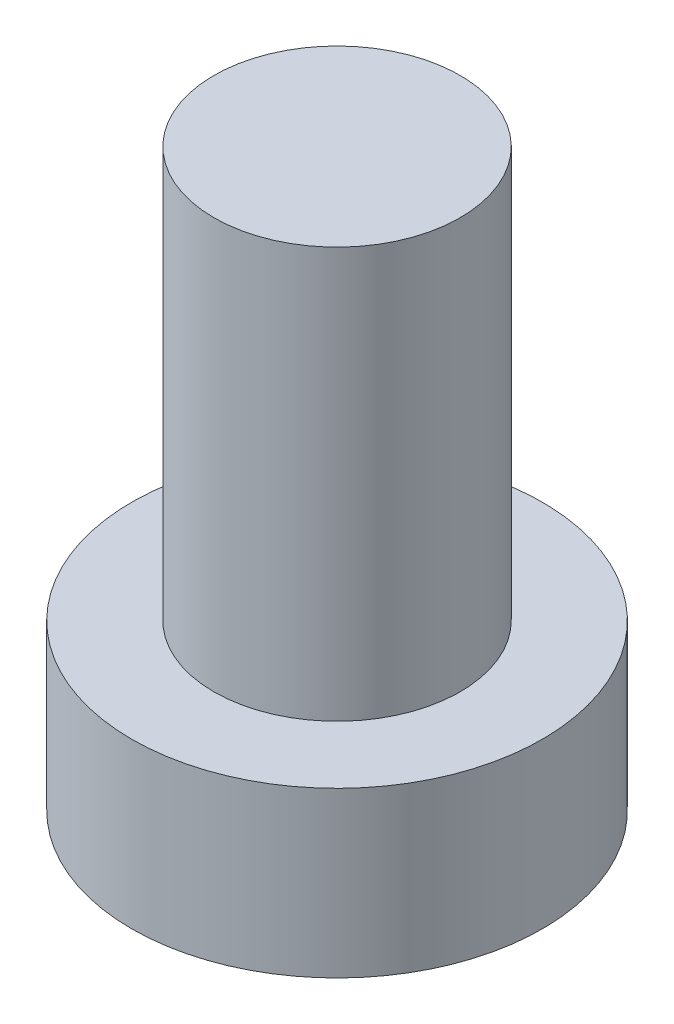
SolidWorks part; units mm, degrees
material "Plain Carbon Steel"
ref_plane "Front Plane" through (0, 0, 0) normal (1, 0, 0) x (0, 1, 0)
ref_plane "Top Plane" through (0, 0, 0) normal (0, 0, 1) x (0, 1, 0)
ref_plane "Right Plane" through (0, 0, 0) normal (0, 1, 0) x (-1, 0, 0)
sketch "Sketch1" plane through (0, 0, 0) normal (0, 1, 0) x (-1, 0, 0)
  circle A0 centre (0, 0) radius 5
  dimension "D1" = 10
extrude "Boss-Extrude1" add sketch "Sketch1" along normal blind 14
sketch "Sketch2" plane through (0, 14, 0) normal (0, 1, 0) x (-1, 0, 0)
  circle A0 centre (0, 0) radius 3
  circle A1 centre (0, 0) radius 5
  circle A2 centre (0, 0) radius 5 construction
  dimension "D1" = 6
extrude "Cut-Extrude1" cut sketch "Sketch2" against normal blind 10
